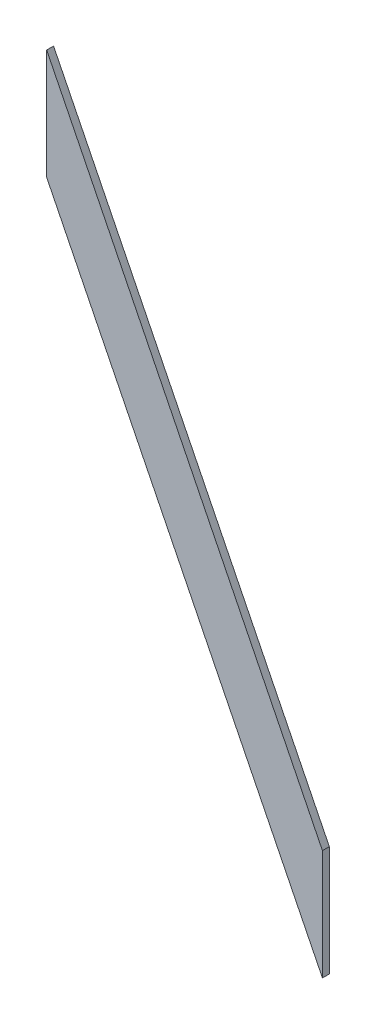
SolidWorks part; units mm, degrees
ref_plane "Front Plane" through (0, 0, 0) normal (0, 0, 1) x (1, 0, 0)
ref_plane "Top Plane" through (0, 0, 0) normal (0, 1, 0) x (1, 0, 0)
ref_plane "Right Plane" through (0, 0, 0) normal (1, 0, 0) x (0, 0, -1)
sketch "Sketch1" plane through (0, 0, 0) normal (0, 0, 1) x (1, 0, 0)
  line L0 (0, -25.4) -> (0, 25.4)
  line L1 (127, -281.2154) -> (127, -230.4154)
  line L2 (0, 25.4) -> (127, -230.4154)
  line L3 (0, -25.4) -> (127, -281.2154)
extrude "Boss-Extrude1" add sketch "Sketch1" along normal blind 3.175
